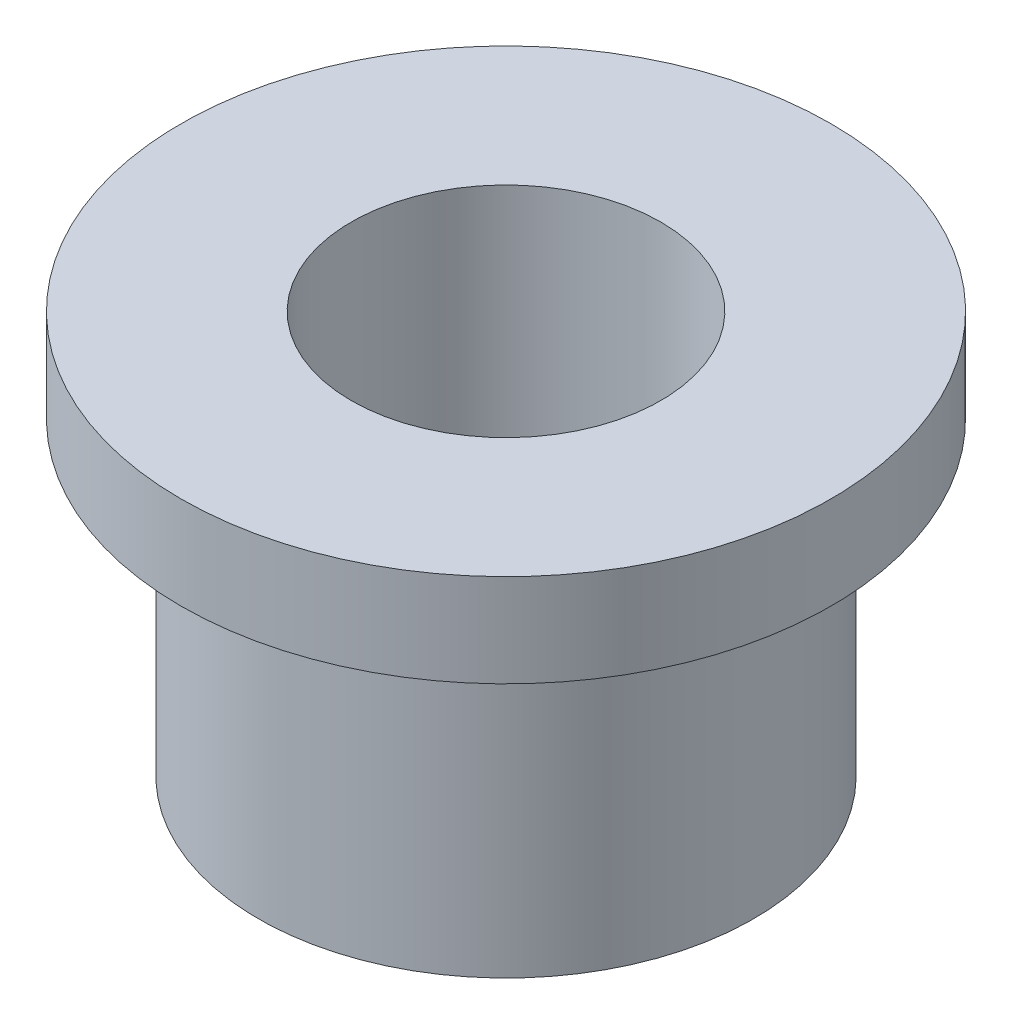
SolidWorks part; units mm, degrees
ref_plane "Front Plane" through (0, 0, 0) normal (0, 0, 1) x (1, 0, 0)
ref_plane "Top Plane" through (0, 0, 0) normal (0, 1, 0) x (1, 0, 0)
ref_plane "Right Plane" through (0, 0, 0) normal (1, 0, 0) x (0, 0, -1)
sketch "Sketch1" plane through (0, 0, 0) normal (0, 0, 1) x (1, 0, 0)
  line L0 (0, 0) -> (0, 5.4195) construction
  line L1 (2.5, 0) -> (2.5, 6.5)
  line L2 (2.5, 6.5) -> (5.25, 6.5)
  line L3 (5.25, 6.5) -> (5.25, 5)
  line L4 (5.25, 5) -> (4, 5)
  line L5 (4, 5) -> (4, 0)
  line L6 (4, 0) -> (2.5, 0)
  dimension "D1" = 8
  dimension "D2" = 5
  dimension "D3" = 1.5
  dimension "D4" = 5
  dimension "D5" = 10.5
revolve "Revolve1" add sketch "Sketch1" angle 360 about L0
